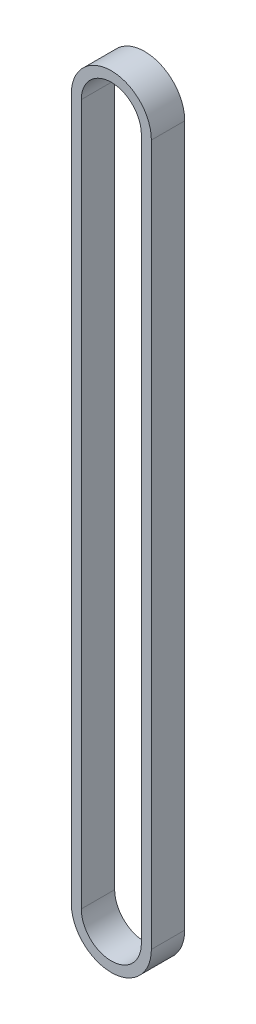
SolidWorks part; units mm, degrees
ref_plane "前视基准面" through (0, 0, 0) normal (0, 0, 1) x (1, 0, 0)
ref_plane "上视基准面" through (0, 0, 0) normal (0, 1, 0) x (1, 0, 0)
ref_plane "右视基准面" through (0, 0, 0) normal (1, 0, 0) x (0, 0, -1)
sketch "草图1" plane through (0, 0, 0) normal (0, 0, 1) x (1, 0, 0)
  line L0 (0, 0) -> (0, -210) construction
  line L1 (12, 0) -> (12, -210)
  line L2 (-12, 0) -> (-12, -210)
  line L3 (0, 0) -> (0, -210) construction
  line L4 (9, 0) -> (9, -210)
  line L5 (-9, 0) -> (-9, -210)
  arc A0 (12, 0) -> (-12, 0) centre (0, 0) ccw
  arc A1 (-12, -210) -> (12, -210) centre (0, -210) ccw
  arc A2 (9, 0) -> (-9, 0) centre (0, 0) ccw
  arc A3 (-9, -210) -> (9, -210) centre (0, -210) ccw
  point P3 (0, -105)
  point P10 (0, -105)
  dimension "D3" = 9
  dimension "D1" = 210
extrude "凸台-拉伸1" add sketch "草图1" along normal blind 10
